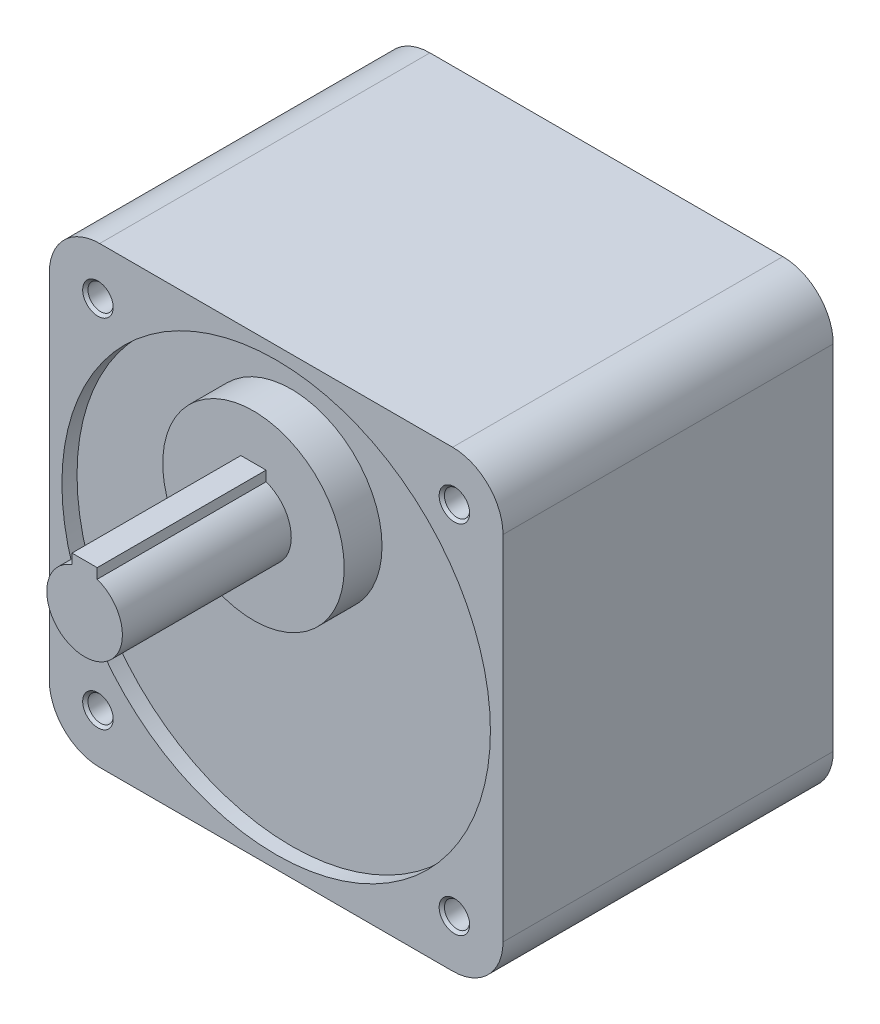
SolidWorks part; units mm, degrees
ref_plane "前视基准面" through (0, 0, 0) normal (0, 0, 1) x (1, 0, 0)
ref_plane "上视基准面" through (0, 0, 0) normal (0, 1, 0) x (1, 0, 0)
ref_plane "右视基准面" through (0, 0, 0) normal (1, 0, 0) x (0, 0, -1)
sketch "草图1" plane through (0, 0, 0) normal (0, 0, 1) x (1, 0, 0)
  line L1 (0, 0) -> (90, 0)
  line L2 (0, 0) -> (0, -90)
  line L3 (0, -90) -> (90, -90)
  line L4 (90, 0) -> (90, -90)
  dimension "D1" = 90
  dimension "D2" = 90
extrude "凸台-拉伸2" add sketch "草图1" along normal blind 65.5
sketch "草图2" plane through (0, 0, 65.5) normal (0, 0, 1) x (1, 0, 0)
  line L0 (45, 0) -> (45, -90) construction
  line L1 (90, 0) -> (0, 0) construction
  line L2 (0, -90) -> (90, -90) construction
  circle A1 centre (45, -45) radius 42.5
  dimension "D1" = 85
extrude "切除-拉伸1" cut sketch "草图2" against normal blind 3
sketch "草图3" plane through (0, 0, 62.5) normal (0, 0, 1) x (1, 0, 0)
  line L0 (0, -45) -> (90, -45) construction
  line L1 (0, 0) -> (0, -90) construction
  line L2 (90, -90) -> (90, 0) construction
  line L3 (45, -45) -> (45, -9) construction
  circle A0 centre (45, -27) radius 18
  dimension "D1" = 36
extrude "凸台-拉伸3" add sketch "草图3" along normal blind 7.5
sketch "草图4" plane through (0, 0, 70) normal (0, 0, 1) x (1, 0, 0)
  line L0 (45, -45) -> (45, -27) construction
  circle A0 centre (45, -27) radius 18 construction
  circle A1 centre (45, -27) radius 18 construction
  circle A2 centre (45, -27) radius 7.5
  dimension "D2" = 15
  dimension "D1" = 18
extrude "凸台-拉伸4" add sketch "草图4" along normal blind 33.5
sketch "草图5" plane through (0, 0, 103.5) normal (0, 0, 1) x (1, 0, 0)
  line L6 (42.5, -19.9289) -> (42.5, -17.9289)
  line L7 (47.5, -19.9289) -> (47.5, -17.9289)
  line L8 (42.5, -17.9289) -> (47.5, -17.9289)
  circle A3 centre (45, -27) radius 7.5 construction
  arc A4 (47.5, -19.9289) -> (42.5, -19.9289) centre (45, -27) ccw
  dimension "D3" = 2
  dimension "D4" = 2
extrude "凸台-拉伸5" add sketch "草图5" against normal up to next
sketch "草图6" plane through (0, 0, 65.5) normal (0, 0, 1) x (1, 0, 0)
  line L0 (45, -45) -> (0, 0) construction
  line L1 (45, -45) -> (90, 0) construction
  line L2 (45, -45) -> (0, -90) construction
  line L3 (45, -45) -> (90, -90) construction
  circle A0 centre (45, -45) radius 50 construction
  dimension "D1" = 100
hole_wizard "M6 螺纹孔1" positions "草图7" profile "草图8" tap size "M6" standard "GB"
sketch "草图7" plane through (0, 0, 65.5) normal (0, 0, 1) x (1, 0, 0)
  line L0 (45, -45) -> (0, 0) construction
  line L1 (45, -45) -> (90, 0) construction
  line L2 (45, -45) -> (0, -90) construction
  line L3 (45, -45) -> (90, -90) construction
  circle A0 centre (45, -45) radius 50 construction
  point P0 (9.6447, -9.6447)
  point P6 (80.3553, -9.6447)
  point P10 (9.6447, -80.3553)
  point P14 (80.3553, -80.3553)
sketch "草图8" plane through (9.6447, -9.6447, 65.5) normal (1, 0, 0) x (0, -1, 0)
  line L0 (0, 0) -> (0, 18.5022)
  line L1 (0, 18.5022) -> (2.5, 17)
  line L2 (2.5, 17) -> (2.5, 0.525)
  line L3 (2.5, 0.525) -> (3.025, 0)
  line L5 (3.025, 0) -> (0, 0)
  line L6 (-2.5, 0.525) -> (-3.025, 0) construction
  line L10 (0, 18.5022) -> (-2.5, 17) construction
  line L11 (0, -6.35) -> (0, 107.95) construction
  dimension "螺纹孔钻头直径" = 5
  dimension "螺纹孔钻头深度" = 17
  dimension "近端锥形沉头孔直径" = 6.05
  dimension "近端锥形沉头孔角度" = 90
  dimension "导头角度" = 118
cosmetic thread "孔螺纹线1" parameters "D1"=12, "D2"=6
cosmetic thread "孔螺纹线2" parameters "D1"=12, "D2"=6
cosmetic thread "孔螺纹线3" parameters "D1"=12, "D2"=6
cosmetic thread "孔螺纹线4" parameters "D1"=12, "D2"=6
fillet "圆角1" radius 10 4 edges at (90, -90, 32.75) (0, -90, 32.75) (90, 0, 32.75) (0, 0, 32.75)
sketch "草图10" plane through (0, 0, 0) normal (0, 0, -1) x (-1, 0, 0)
  line L0 (-87.0711, -2.9289) -> (-2.9289, -87.0711) construction
  line L3 (-2.9289, -2.9289) -> (-87.0711, -87.0711) construction
  circle A0 centre (-44.9166, -45) radius 50 construction
  arc A1 (-80, 0) -> (-90, -10) centre (-80, -10) ccw construction
  arc A2 (-10, -90) -> (0, -80) centre (-10, -80) ccw construction
  arc A3 (0, -10) -> (-10, 0) centre (-10, -10) ccw construction
  arc A4 (-90, -80) -> (-80, -90) centre (-80, -80) ccw construction
  point P20 (-80.3136, -9.6864)
  point P22 (-9.603, -9.603)
  point P24 (-80.3136, -80.3136)
  point P26 (-9.603, -80.397)
  dimension "D1" = 100
hole_wizard "M6 螺纹孔2" positions "草图10" profile "草图11" tap size "M6" standard "GB"
sketch "草图11" plane through (9.603, -80.397, 0) normal (1, 0, 0) x (0, 1, 0)
  line L0 (0, 0) -> (0, 18.5022)
  line L1 (0, 18.5022) -> (2.5, 17)
  line L2 (2.5, 17) -> (2.5, 0.525)
  line L3 (2.5, 0.525) -> (3.025, 0)
  line L5 (3.025, 0) -> (0, 0)
  line L6 (-2.5, 0.525) -> (-3.025, 0) construction
  line L10 (0, 18.5022) -> (-2.5, 17) construction
  line L11 (0, -6.35) -> (0, 107.95) construction
  dimension "螺纹孔钻头直径" = 5
  dimension "螺纹孔钻头深度" = 17
  dimension "近端锥形沉头孔直径" = 6.05
  dimension "近端锥形沉头孔角度" = 90
  dimension "导头角度" = 118
cosmetic thread "孔螺纹线5" parameters "D1"=12, "D2"=6
cosmetic thread "孔螺纹线6" parameters "D1"=12, "D2"=6
cosmetic thread "孔螺纹线7" parameters "D1"=12, "D2"=6
cosmetic thread "孔螺纹线8" parameters "D1"=12, "D2"=6
